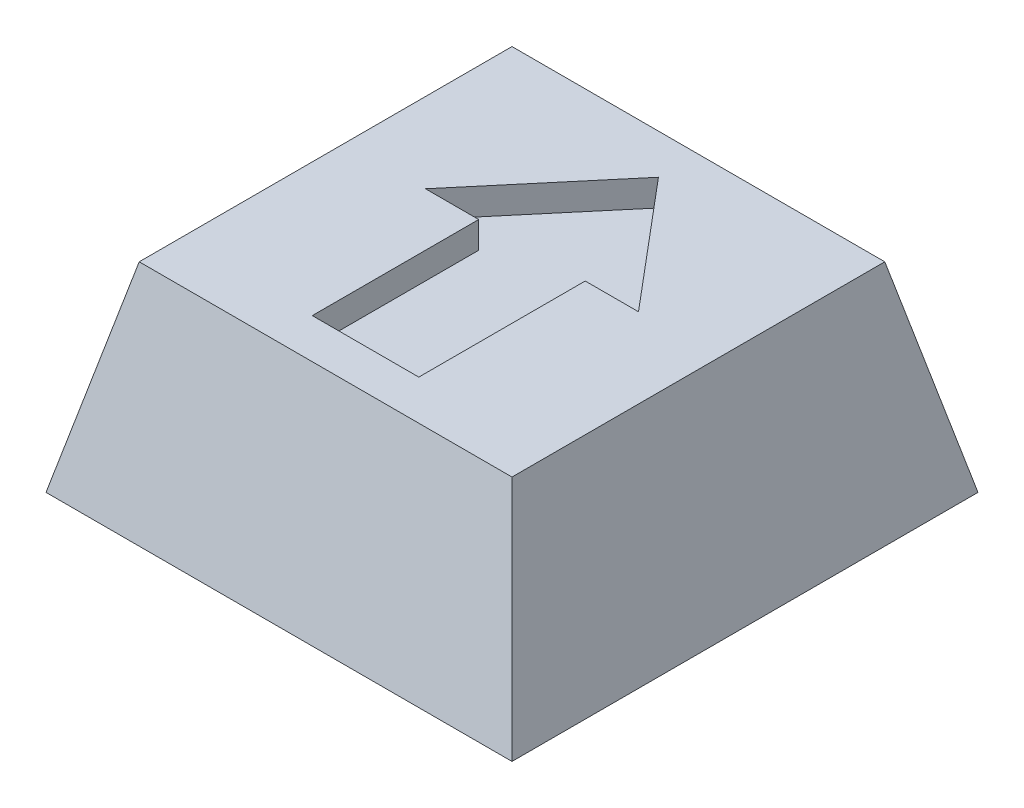
SolidWorks part; units mm, degrees
ref_plane "Front Plane" through (0, 0, 0) normal (0, 0, 1) x (1, 0, 0)
ref_plane "Top Plane" through (0, 0, 0) normal (0, 1, 0) x (1, 0, 0)
ref_plane "Right Plane" through (0, 0, 0) normal (1, 0, 0) x (0, 0, -1)
sketch "Sketch1" plane through (0, 0, 0) normal (0, 1, 0) x (1, 0, 0)
  line L1 (0, 0) -> (7, 0)
  line L2 (0, 0) -> (0, 7)
  line L3 (0, 7) -> (7, 7)
  line L4 (7, 0) -> (7, 7)
  dimension "D1" = 7
  dimension "D2" = 7
extrude "Boss-Extrude1" add sketch "Sketch1" along normal blind 3
sketch "Sketch2" plane through (0, 0, 0) normal (0, 0, 1) x (1, 0, 0)
  line L0 (0, 0) -> (0.7, 3)
  line L1 (0, 3) -> (7, 3) construction
  line L2 (0.7, 3) -> (0, 3)
  line L3 (0, 3) -> (0, 0)
  line L4 (7, 0) -> (6.3, 3)
  line L5 (6.3, 3) -> (7, 3)
  line L6 (7, 3) -> (7, 0)
  dimension "D1" = 0.7
  dimension "D2" = 0.7
extrude "Cut-Extrude1" cut sketch "Sketch2" against normal blind 7
sketch "Sketch3" plane through (0, 0, 0) normal (1, 0, 0) x (0, 0, -1)
  line L0 (0, 0) -> (0.7, 3)
  line L1 (7, 3) -> (0, 3) construction
  line L2 (0.7, 3) -> (0, 3)
  line L3 (0, 3) -> (0, 0)
  line L4 (7, 3) -> (6.3, 3)
  line L5 (6.3, 3) -> (7, 0)
  line L6 (7, 3) -> (7, 0)
  dimension "D1" = 0.7
  dimension "D2" = 0.7
extrude "Cut-Extrude2" cut sketch "Sketch3" along normal blind 11
sketch "Sketch4" plane through (0, 0, 0) normal (0, -1, 0) x (1, 0, 0)
  line L0 (3.5, 0) -> (3.5, -7) construction
  line L1 (0, 0) -> (7, 0) construction
  line L2 (7, -7) -> (0, -7) construction
  line L3 (0, -3.5) -> (7, -3.5) construction
  line L4 (0, -7) -> (0, 0) construction
  line L5 (7, 0) -> (7, -7) construction
  circle A0 centre (3.5, -3.5) radius 1.8
  dimension "D1" = 3.6
extrude "Cut-Extrude3" cut sketch "Sketch4" against normal blind 0.8
sketch "Sketch5" plane through (0, 3, 0) normal (0, 1, 0) x (1, 0, 0)
  line L0 (4.3, 3.8) -> (5.1, 3.8)
  line L1 (2.7, 3.8) -> (4.3, 3.8)
  line L2 (2.7, 3.8) -> (2.7, 1.3)
  line L3 (2.7, 1.3) -> (4.3, 1.3)
  line L4 (4.3, 3.8) -> (4.3, 1.3)
  line L5 (5.1, 3.8) -> (3.5, 5.7)
  line L6 (3.5, 5.7) -> (1.9, 3.8)
  line L7 (1.9, 3.8) -> (2.7, 3.8)
  line L8 (6.3, 6.3) -> (6.3, 0.7) construction
  line L9 (0.7, 6.3) -> (0.7, 0.7) construction
  line L10 (6.3, 0.7) -> (0.7, 0.7) construction
  line L11 (6.3, 6.3) -> (0.7, 6.3) construction
  point P11 (3.5, 3.8)
  dimension "D1" = 0.8
  dimension "D2" = 0.8
  dimension "D3" = 2
  dimension "D4" = 2
  dimension "D5" = 0
  dimension "D6" = 0.6
  dimension "D7" = 0.6
  dimension "D8" = 2.5
extrude "Cut-Extrude4" cut sketch "Sketch5" against normal blind 0.4 contours L6 L7 L1 L0 L5 | L4 L1 L2 L3
